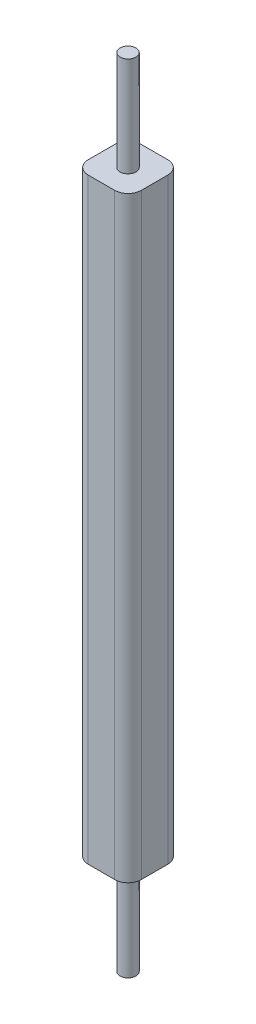
SolidWorks part; units mm, degrees
ref_plane "前视基准面" through (0, 0, 0) normal (0, 0, 1) x (1, 0, 0)
ref_plane "上视基准面" through (0, 0, 0) normal (0, 1, 0) x (1, 0, 0)
ref_plane "右视基准面" through (0, 0, 0) normal (1, 0, 0) x (0, 0, -1)
sketch "草图1" plane through (0, 0, 0) normal (0, 1, 0) x (1, 0, 0)
  circle A0 centre (0, 0) radius 6
  dimension "D1" = 12
extrude "凸台-拉伸1" add sketch "草图1" along normal mid plane 600
sketch "草图2" plane through (0, 0, 0) normal (0, 1, 0) x (1, 0, 0)
  line L1 (-20, 20) -> (20, 20)
  line L2 (-20, 20) -> (-20, -20)
  line L3 (-20, -20) -> (20, -20)
  line L4 (20, 20) -> (20, -20)
  line L5 (-20, 20) -> (20, -20) construction
  line L6 (-20, -20) -> (20, 20) construction
  point P0 (0, 0)
  dimension "D1" = 40
  dimension "D2" = 40
extrude "凸台-拉伸2" add sketch "草图2" along normal mid plane 450
fillet "圆角1" radius 10 4 edges at (20, 0, 20) (-20, 0, 20) (20, 0, -20) (-20, 0, -20)
